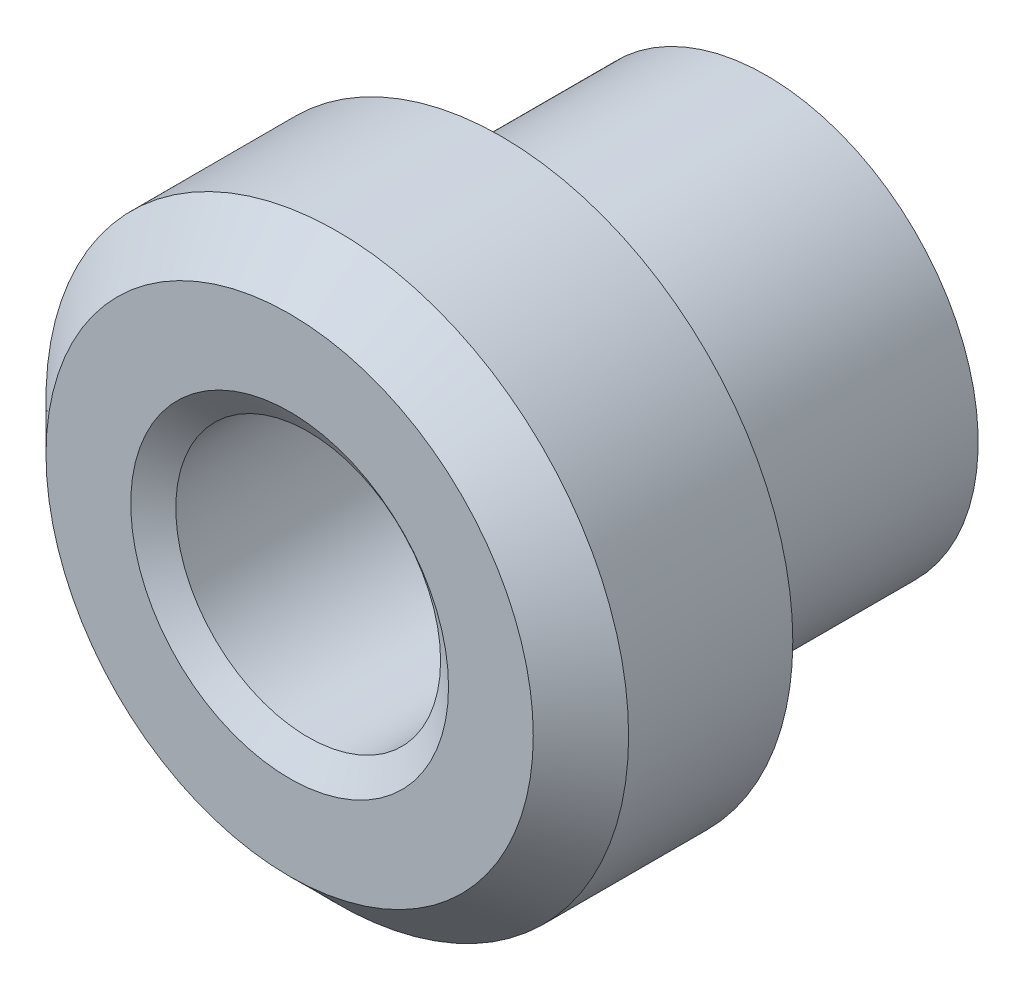
SolidWorks part; units mm, degrees
material "Chrome Stainless Steel"
ref_plane "Plane1" through (0, 0, 0) normal (0, 0, 1) x (1, 0, 0)
ref_plane "Plane2" through (0, 0, 0) normal (0, 1, 0) x (1, 0, 0)
ref_plane "Plane3" through (0, 0, 0) normal (1, 0, 0) x (0, 0, -1)
sketch "BaseNutSke" plane through (0, 0, 0) normal (0, 0, 1) x (1, 0, 0)
  circle A0 centre (0, 0) radius 1.25
  circle A1 centre (0, 0) radius 2.75
  dimension "Tap_drill" = 2.5
  dimension "Outerdia" = 5.5
extrude "BaseNut" add sketch "BaseNutSke" against normal blind 4.5
sketch "EndChSke"
  line L0 (4.4746, 1.5) -> (4.282, 1.225)
  line L1 (4.5254, 1.5) -> (4.4746, 1.5)
  line L2 (4.5254, 1.5) -> (4.5254, 1.225)
  line L3 (4.5254, 1.225) -> (4.282, 1.225)
  line L6 (-0.0508, 1.5) -> (0, 1.5)
  line L7 (0, 1.5) -> (0.1926, 1.225)
  line L9 (0.1926, 1.225) -> (-0.0508, 1.225)
  line L10 (-0.0508, 1.225) -> (-0.0508, 1.5)
  line L11 (25.0375, 0) -> (38.388, 0) construction
  line L12 (4.5, 0) -> (0, 0) construction
pattern_linear "ThdSchPat" [suppressed]
revolve "ThreadSchematic" cut sketch "ThdSchSke"
sketch "ThdSchSke" plane through (0, 0, 0) normal (0, 1, 0) x (1, 0, 0)
  line L0 (-1.5, 0.025) -> (-1.25, 0.2001)
  line L1 (-1.25, 0.2001) -> (-0.625, 0.2001)
  line L2 (-0.625, 0.2001) -> (-0.625, -0.1501)
  line L3 (-0.625, -0.1501) -> (-1.25, -0.1501)
  line L4 (-1.25, -0.1501) -> (-1.5, 0.025)
  line L5 (-2.675, 0.275) -> (3.675, 0.275) construction
  line L6 (0, 0.275) -> (0, 6.35) construction
  line L7 (0, 4.2995) -> (0, 0.1751) construction
  dimension "D1" = 35
  dimension "VeeAngle" = 70
  dimension "SideAngle" = 235
  dimension "D2" = 0.0508
  dimension "OverCut" = 1.25
  dimension "Tap_Drill" = 2.5
  dimension "Advance" = 0.4944
  dimension "Thread_major" = 3
  dimension "Num_threads" = 10
  dimension "D4" = 50
  dimension "Offset1" = 4.5254
  dimension "ThreadMajor" = 1.5
  dimension "ChamferDepth" = 0.275
  dimension "Offset2" = 4.5762
revolve "EndChamfer" cut sketch "EndChSke" angle 360 about L11
chamfer "Chamfer1" distance 0.45 angle 45 1 edges at (2.75, 0, 0)
sketch "Sketch1" plane through (0, 0, -4.5) normal (0, 0, -1) x (-1, 0, 0)
  circle A0 centre (0, 0) radius 2
  dimension "D1" = 4
extrude "Cut-Extrude1" cut sketch "Sketch1" against normal blind 2.5 flip side to cut
equation "\"Tap_drill@ThdSchSke\" = \"Tap_drill@BaseNutSke\""
equation "\"Overcut@ThdSchSke\" = \"Tap_drill@ThdSchSke\" * 0.5"
equation "\"Num_threads@ThdSchPat\" = int(  ( \"Thickness@BaseNut\" - 0.0508 ) / \"Advance@ThdSchSke\" + 0.999 )  + 1"
equation "\"Advance@ThdSchPat\" = ( \"Thickness@BaseNut\" - 0.0508 ) /  (\"Num_threads@ThdSchPat\" - 1) 'relax it"
equation "' \"Num_threads@ThdSchPat\" = \"Num_threads@ThdSchPat\" - sgn( \"Num_threads@ThdSchPat\" - 1) '---chamfered tips only---"
equation "\"ThreadMajor@EndChSke\" = \"Thread_major@ThdSchSke\" * 0.5"
equation "\"ChamferDepth@EndChSke\" = (\"Thread_major@ThdSchSke\" - \"Tap_drill@BaseNutSke\") * 0.55"
equation "\"Offset1@EndChSke\" = \"Thickness@BaseNut\" + 0.0254"
equation "\"Offset2@EndChSke\" = \"Offset1@EndChSke\" + 0.0508"
equation "\"Chamfer_len@Chamfer1\" = 0.1 * \"Thickness@BaseNut\""
